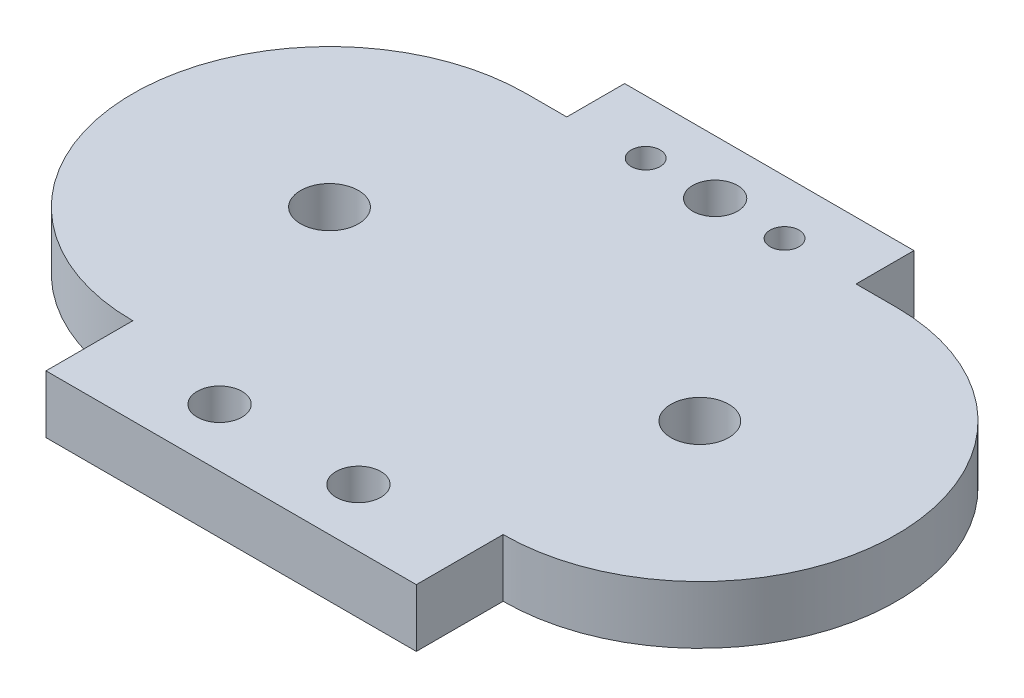
SolidWorks part; units mm, degrees
material "TPU 74D"
ref_plane "Front Plane" through (0, 0, 0) normal (0, 0, 1) x (1, 0, 0)
ref_plane "Top Plane" through (0, 0, 0) normal (0, 1, 0) x (1, 0, 0)
ref_plane "Right Plane" through (0, 0, 0) normal (1, 0, 0) x (0, 0, -1)
sketch "Sketch1" plane through (0, 0, 0) normal (0, 1, 0) x (1, 0, 0)
  line L0 (-40.64, 0) -> (40.64, 0) construction
  line L1 (0, 34.29) -> (0, -31.75) construction
  line L2 (20.32, 0) -> (7.62, 21.997) construction
  line L3 (-20.32, 0) -> (-7.62, 21.997) construction
  line L11 (-20.32, 21.59) -> (-15.875, 21.59)
  line L13 (-15.875, 21.59) -> (-15.875, 27.94)
  line L14 (-15.875, 27.94) -> (15.875, 27.94)
  line L15 (15.875, 21.59) -> (15.875, 27.94)
  line L16 (20.32, 21.59) -> (15.875, 21.59)
  line L17 (-20.32, -21.59) -> (-20.32, -31.115)
  line L18 (-20.32, -31.115) -> (20.32, -31.115)
  line L19 (20.32, -31.115) -> (20.32, -21.59)
  circle A3 centre (20.32, 0) radius 3.175
  circle A4 centre (7.62, 21.997) radius 1.5875
  circle A5 centre (-20.32, 0) radius 3.175
  circle A6 centre (-7.62, 21.997) radius 1.5875
  arc A10 (-20.32, 21.59) -> (-20.32, -21.59) centre (-20.32, 0) ccw
  arc A11 (20.32, 21.59) -> (20.32, -21.59) centre (20.32, 0) cw
  point P21 (0, 27.94)
  dimension "D1" = 25.4
  dimension "D4" = 6.35
  dimension "D5" = 3.175
  dimension "D6" = 21.59
  dimension "D2" = 60
  dimension "D3" = 20.32
  dimension "D7" = 6.35
  dimension "D8" = 31.75
  dimension "D9" = 9.525
extrude "Boss-Extrude1" add sketch "Sketch1" along normal blind 6.35
sketch "Sketch4" plane through (0, 6.35, 0) normal (0, 1, 0) x (1, 0, 0)
  line L1 (-20.32, -21.59) -> (-20.32, -31.115) construction
  line L2 (-20.32, -31.115) -> (20.32, -31.115) construction
  line L3 (20.32, -31.115) -> (20.32, -21.59) construction
  point P0 (-7.62, 21.997)
  point P1 (0, 21.997)
  point P2 (20.32, 0)
  point P4 (7.62, -24.765)
  point P8 (7.62, 21.997)
  point P9 (-20.32, 0)
  point P10 (-7.62, -24.765)
  dimension "D1" = 12.7
  dimension "D2" = 6.35
  dimension "D3" = 12.7
  dimension "D4" = 7.62
hole_wizard "#10 (0.1935) Diameter Hole1" positions "Sketch5" profile "Sketch6" hole size "#10" standard "ANSI Inch" end condition through all
sketch "Sketch5" plane through (0, 6.35, 0) normal (0, 1, 0) x (1, 0, 0)
  point P6 (0, 21.997)
  point P9 (0, 21.997)
  point P11 (-7.62, -24.765)
  point P14 (7.62, -24.765)
  point P20 (0, 0)
  point P21 (0, 0)
  point P22 (0, 0)
sketch "Sketch6" plane through (0, 6.35, -21.997) normal (1, 0, 0) x (0, 0, 1)
  line L0 (0, 0) -> (0, 6.35)
  line L1 (0, 6.35) -> (2.4574, 6.35)
  line L2 (2.4574, 6.35) -> (2.4574, 0)
  line L5 (2.4574, 0) -> (0, 0)
  line L11 (0, -6.35) -> (0, 107.95) construction
  dimension "Thru Hole Dia." = 4.9149
  dimension "Thru Hole Depth" = 6.35
shell "Shell2" [suppressed] thickness 2.54
sketch "Sketch3" [suppressed] plane through (0, 0, 0) normal (0, -1, 0) x (1, 0, 0)
  line L0 (-36.478, -40.64) -> (-27.7857, 8.89)
  line L1 (-27.7857, 8.89) -> (27.7857, 8.89)
  line L2 (27.7857, 8.89) -> (36.478, -40.64)
  line L3 (36.478, -40.64) -> (-36.478, -40.64)
  circle A0 centre (-20.32, 0) radius 8.89 construction
  circle A1 centre (20.32, 0) radius 8.89 construction
extrude "Cut-Extrude1" [suppressed] cut sketch "Sketch3" against normal up to surface (2.54 mm away)
